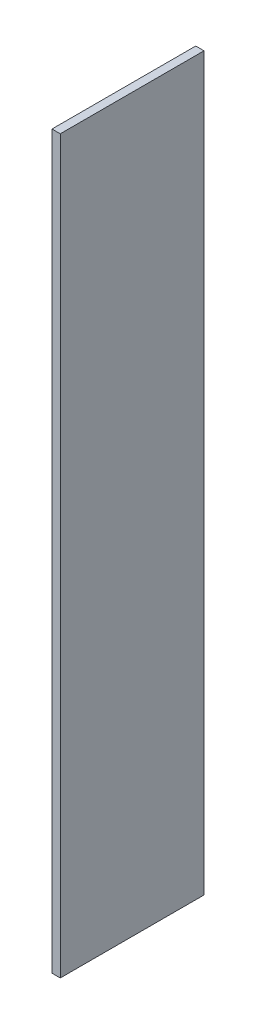
SolidWorks part; units mm, degrees
ref_plane "Front Plane" through (0, 0, 0) normal (0, 0, 1) x (1, 0, 0)
ref_plane "Top Plane" through (0, 0, 0) normal (0, 1, 0) x (1, 0, 0)
ref_plane "Right Plane" through (0, 0, 0) normal (1, 0, 0) x (0, 0, -1)
sketch "Sketch1" plane through (0, 0, 0) normal (1, 0, 0) x (0, 0, -1)
  line L1 (-28.2194, 143.51) -> (28.2194, 143.51)
  line L2 (-28.2194, 143.51) -> (-28.2194, -143.51)
  line L3 (-28.2194, -143.51) -> (28.2194, -143.51)
  line L4 (28.2194, 143.51) -> (28.2194, -143.51)
  line L5 (-28.2194, 143.51) -> (28.2194, -143.51) construction
  line L6 (-28.2194, -143.51) -> (28.2194, 143.51) construction
  point P0 (0, 0)
  dimension "D1" = 56.4388
  dimension "D2" = 287.02
extrude "Boss-Extrude1" add sketch "Sketch1" along normal blind 3.2512
equation "\"motor offset\"=6mm"
equation "\"thickness0.25\"=0.225in"
equation "\"thickness0.125\"=0.122in"
equation "\"thickness_acrylic0.1\"= 0.1in"
equation "\"D1@Sketch1\"=\"thickness_acrylic0.1\"+\"thickness0.125\"+2"
